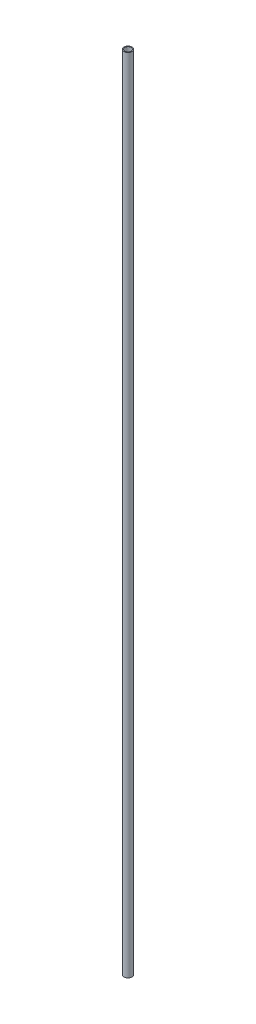
SolidWorks part; units mm, degrees
ref_plane "Frontal Plane" through (0, 0, 0) normal (0, 0, 1) x (1, 0, 0)
ref_plane "Horizontal Plane" through (0, 0, 0) normal (0, 1, 0) x (1, 0, 0)
ref_plane "Profile Plane" through (0, 0, 0) normal (1, 0, 0) x (0, 0, -1)
sketch "Sketch1" plane through (0, 0, 0) normal (0, 1, 0) x (1, 0, 0)
  circle A0 centre (0, 0) radius 5
  circle A1 centre (0, 0) radius 4
  dimension "D1" = 10
  dimension "D2" = 8
extrude "Boss-Extrude1" add sketch "Sketch1" against normal blind 1000
equation "\"BaseL\"= 6ft"
equation "\"BaseW\"= 5.5in"
equation "\"BaseThickness\"= 1in"
equation "\"RailGap\"= 4cm"
equation "\"SlidePlateL\"= 8cm"
equation "\"SlidePlateW\"= 11cm"
equation "\"SlidePlateThickness\"= 5mm"
equation "\"SlidePlateClearance\"= 1cm"
equation "\"BoxThickness\"= .5cm"
equation "\"BoxX\"= \"RailGap\" + 30mm"
equation "\"BoxH\"= 2cm + \"SlidePlateClearance\" + \"SlidePlateThickness\" + 3cm"
equation "\"PulleyRadius\"= 15.1mm"
equation "\"PulleyH\"= 30mm + 21.4056mm - 2.5mm"
equation "\"PulleyShaftDiameter\"= .3125in"
equation "\"PulleyShaftL\"= 4in"
equation "\"PulleyShaft2L\"= 3in"
equation "\"MotorL\"= 4.43in"
equation "\"MotorRadius\"= 1.291in"
equation "\"MotorShaftRadius\"= .15625in"
equation "\"MotorShaftL\"= 1.75in"
equation "\"HeadstoneThickness\"= 7.5mm"
equation "\"BeltL\"= 1500mm + \"80\""
equation "\"BeltThickness\"= 2.5mm"
equation "\"BeltW\"= .375in"
equation "\"BeltLockH\"= \"PulleyH\" + 19.4056mm - (\"SlidePlateThickness\" + \"SlidePlateClearance\" + 15mm + 5mm)"
equation "\"EncoderL\"= 33mm"
equation "\"EncoderRadius\"= 19mm"
equation "\"EncoderShaftRadius\"= 3mm"
equation "\"EncoderShaftL\"= 15mm"
equation "\"PendulumShaftL\"= \"100mm\" "
equation "\"PendulumShaftRadius\"= 3mm"
equation "\"RodL\"= 39in"
equation "\"RodRadius\"= 3mm"
equation "\"D1@Boss-Extrude1\"=\"RodL\""
